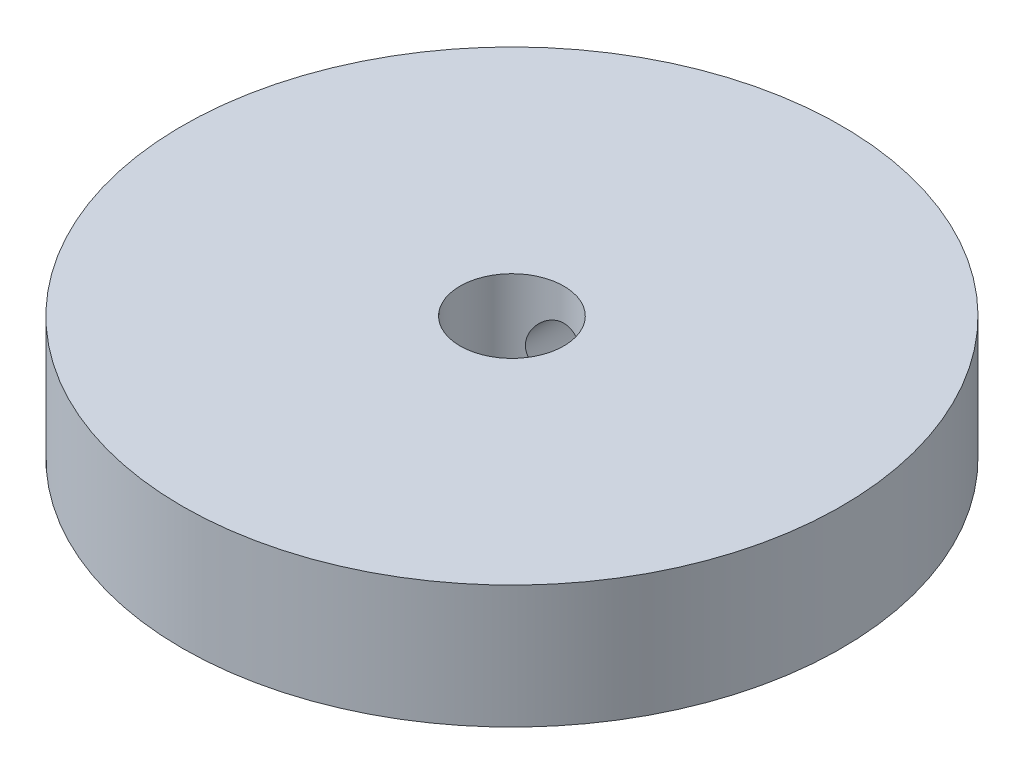
SolidWorks part; units mm, degrees
ref_plane "Front Plane" through (0, 0, 0) normal (0, 0, 1) x (1, 0, 0)
ref_plane "Top Plane" through (0, 0, 0) normal (0, 1, 0) x (1, 0, 0)
ref_plane "Right Plane" through (0, 0, 0) normal (1, 0, 0) x (0, 0, -1)
sketch "Sketch1" plane through (0, 0, 0) normal (0, 1, 0) x (1, 0, 0)
  circle A0 centre (0, 0) radius 13.3985
  circle A1 centre (0, 0) radius 2.11
  dimension "D1" = 26.797
  dimension "D2" = 4.22
extrude "Boss-Extrude1" add sketch "Sketch1" along normal mid plane 5
sketch "Sketch2" plane through (0, 0, 0) normal (0, 0, 1) x (1, 0, 0)
  circle A0 centre (0, 0) radius 1.1929
extrude "Cut-Extrude1" cut sketch "Sketch2" against normal through all
